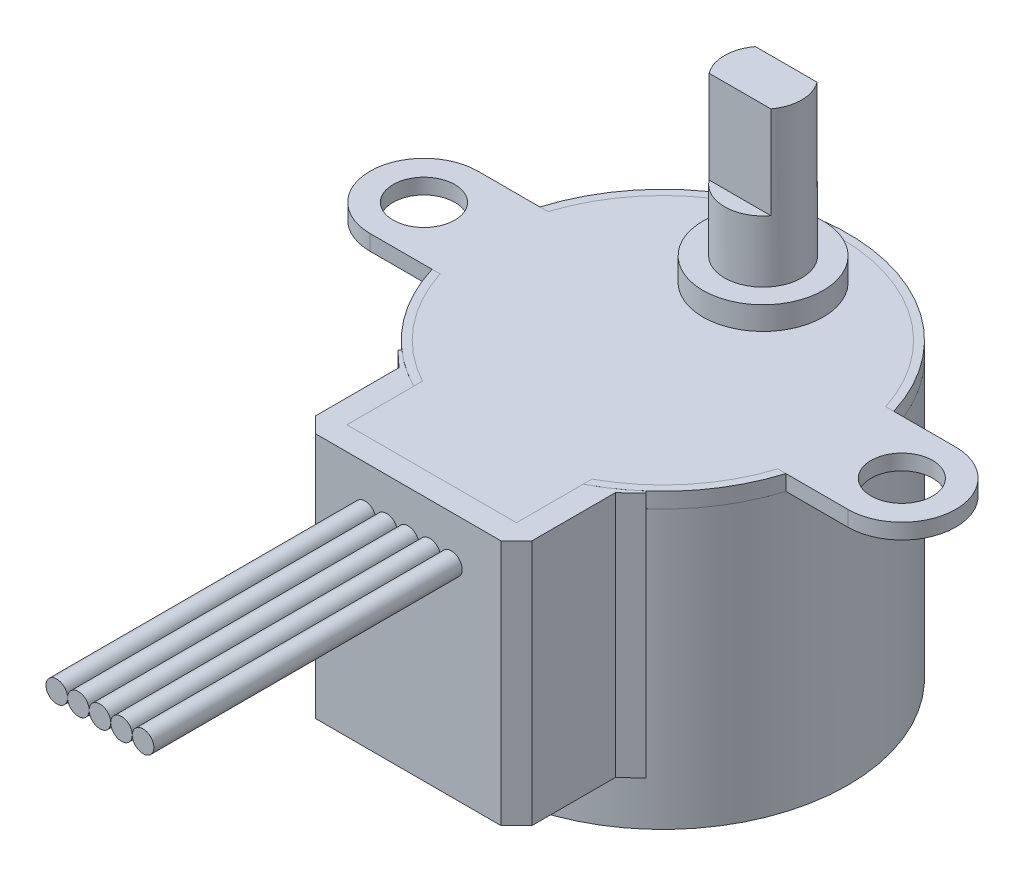
SolidWorks part; units mm, degrees
ref_plane "Front Plane" through (0, 0, 0) normal (0, 0, 1) x (1, 0, 0)
ref_plane "Top Plane" through (0, 0, 0) normal (0, 1, 0) x (1, 0, 0)
ref_plane "Right Plane" through (0, 0, 0) normal (1, 0, 0) x (0, 0, -1)
sketch "Sketch1" plane through (0, 0, 0) normal (0, 1, 0) x (1, 0, 0)
  circle A0 centre (0, 0) radius 12
  dimension "D1" = 24
extrude "Boss-Extrude1" add sketch "Sketch1" along normal blind 18
sketch "Sketch2" plane through (0, 18, 0) normal (0, 1, 0) x (1, 0, 0)
  line L0 (0, 16.9887) -> (0, 11.5) construction
  line L1 (10.9545, 3.5) -> (15.5, 3.5)
  line L2 (15.5, -3.5) -> (10.9545, -3.5)
  line L3 (-15.5, -3.5) -> (-10.9545, -3.5)
  line L4 (-10.9545, 3.5) -> (-15.5, 3.5)
  line L5 (-5.5, -10.0995) -> (-5.5, -15)
  line L6 (-5.5, -15) -> (5.5, -15)
  line L7 (5.5, -10.0995) -> (5.5, -15)
  line L8 (0, -11.5) -> (0, -20.5487) construction
  arc A0 (10.9545, 3.5) -> (-10.9545, 3.5) centre (0, 0) ccw
  circle A1 centre (15.5, 0) radius 2
  arc A2 (15.5, -3.5) -> (15.5, 3.5) centre (15.5, 0) ccw
  arc A3 (-15.5, -3.5) -> (-15.5, 3.5) centre (-15.5, 0) cw
  circle A4 centre (-15.5, 0) radius 2
  arc A5 (-10.9545, -3.5) -> (-5.5, -10.0995) centre (0, 0) ccw
  arc A6 (5.5, -10.0995) -> (10.9545, -3.5) centre (0, 0) ccw
  point P20 (0, -15)
  dimension "D1" = 23
  dimension "D3" = 4
  dimension "D2" = 15.5
  dimension "D4" = 3.5
  dimension "D5" = 7
  dimension "D6" = 15
  dimension "D7" = 5.5
extrude "Boss-Extrude2" add sketch "Sketch2" along normal blind 1 separate body
sketch "Sketch3" plane through (0, 18, 0) normal (0, 1, 0) x (1, 0, 0)
  line L0 (-11.4782, 3.5) -> (-10.9545, 3.5)
  line L3 (11.4782, -3.5) -> (10.9545, -3.5)
  line L5 (10.9545, 3.5) -> (11.4782, 3.5)
  line L6 (-10.9545, -3.5) -> (-11.4782, -3.5)
  line L7 (-5.5, -10.0995) -> (-5.5, -10.6654)
  line L8 (-5.5, -10.0995) -> (-5.5, -15) construction
  line L9 (5.5, -10.0995) -> (5.5, -10.6654)
  line L10 (5.5, -15) -> (5.5, -10.0995) construction
  arc A0 (-10.9545, -3.5) -> (-5.5, -10.0995) centre (0, 0) ccw
  circle A1 centre (0, 0) radius 12
  arc A2 (-11.4782, -3.5) -> (-5.5, -10.6654) centre (0, 0) ccw
  arc A3 (10.9545, 3.5) -> (-10.9545, 3.5) centre (0, 0) ccw
  arc A4 (11.4782, 3.5) -> (-11.4782, 3.5) centre (0, 0) ccw
  arc A5 (5.5, -10.0995) -> (10.9545, -3.5) centre (0, 0) ccw
  arc A6 (5.5, -10.6654) -> (11.4782, -3.5) centre (0, 0) ccw
  dimension "D1" = 0
extrude "Boss-Extrude3" add sketch "Sketch3" along normal blind 1 separate body
sketch "Sketch4" plane through (0, 19, 0) normal (0, 1, 0) x (1, 0, 0)
  line L0 (5.5, -15) -> (5.5, -10.0995) construction
  line L1 (-5.5, -15) -> (5.5, -15) construction
  line L2 (-5.5, -10.0995) -> (-5.5, -15) construction
  line L3 (5.5, -15) -> (5.5, -10.6654)
  line L4 (-5.5, -15) -> (5.5, -15)
  line L5 (-5.5, -10.6654) -> (-5.5, -15)
  line L6 (-7.02, -10.0995) -> (-7.02, -15.52)
  line L7 (-6.02, -16.52) -> (6.02, -16.52)
  line L8 (7.02, -15.52) -> (7.02, -10.0995)
  line L9 (-7.02, -10.0995) -> (-8.0447, -9.145)
  line L10 (-8.0447, -9.145) -> (-7.9259, -9.01)
  line L11 (0, 0) -> (0, -6.5603) construction
  line L12 (8.0447, -9.145) -> (7.9259, -9.01)
  line L13 (7.02, -10.0995) -> (8.0447, -9.145)
  line L14 (-5.5, -10.0995) -> (-5.5, -15) construction
  line L15 (5.5, -15) -> (5.5, -10.0995) construction
  line L16 (-7.02, -10.0995) -> (-7.02, -16.52) construction
  line L17 (-7.02, -16.52) -> (7.02, -16.52) construction
  line L18 (-7.02, -15.52) -> (-6.02, -16.52)
  line L19 (7.02, -16.52) -> (7.02, -10.0995) construction
  line L20 (6.02, -16.52) -> (7.02, -15.52)
  arc A0 (-7.9259, -9.01) -> (-5.5, -10.6654) centre (0, 0) ccw
  arc A1 (5.5, -10.6654) -> (7.9259, -9.01) centre (0, 0) ccw
  dimension "D1" = 1.52
extrude "Boss-Extrude4" add sketch "Sketch4" against normal blind 16 separate body
sketch "Sketch5" plane through (0, 3, 0) normal (0, -1, 0) x (1, 0, 0)
  line L12 (-5.5, 10.6654) -> (-5.5, 15)
  line L13 (-5.5, 15) -> (5.5, 15)
  line L14 (5.5, 15) -> (5.5, 10.6654)
  line L15 (7.9259, 9.01) -> (8.0447, 9.145)
  line L16 (8.0447, 9.145) -> (7.02, 10.0995)
  line L17 (7.02, 10.0995) -> (7.02, 15.52)
  line L18 (7.02, 15.52) -> (6.02, 16.52)
  line L19 (6.02, 16.52) -> (-6.02, 16.52)
  line L20 (-6.02, 16.52) -> (-7.02, 15.52)
  line L21 (-7.02, 15.52) -> (-7.02, 10.0995)
  line L22 (-7.02, 10.0995) -> (-8.0447, 9.145)
  line L23 (-8.0447, 9.145) -> (-7.9259, 9.01)
  line L27 (7.9259, 9.01) -> (8.0447, 9.145)
  line L28 (8.0447, 9.145) -> (7.02, 10.0995)
  line L29 (7.02, 10.0995) -> (7.02, 15.52)
  line L30 (7.02, 15.52) -> (6.02, 16.52)
  line L31 (6.02, 16.52) -> (-6.02, 16.52)
  line L32 (-6.02, 16.52) -> (-7.02, 15.52)
  line L33 (-7.02, 15.52) -> (-7.02, 10.0995)
  line L34 (-7.02, 10.0995) -> (-8.0447, 9.145)
  line L35 (-8.0447, 9.145) -> (-7.9259, 9.01)
  arc A0 (7.9259, 9.01) -> (-7.9259, 9.01) centre (0, 0) ccw
  arc A2 (-5.5, 10.6654) -> (-7.9259, 9.01) centre (0, 0) ccw
  arc A3 (7.9259, 9.01) -> (5.5, 10.6654) centre (0, 0) ccw
  arc A4 (-5.5, 10.6654) -> (-7.9259, 9.01) centre (0, 0) ccw
  arc A5 (7.9259, 9.01) -> (5.5, 10.6654) centre (0, 0) ccw
  arc M15 (-7.9259, 9.01) -> (-5.5, 10.6654) centre (0, 0) cw
  line M16 (-5.5, 10.6654) -> (-5.5, 15)
  line M17 (-5.5, 15) -> (5.5, 15)
  line M18 (5.5, 15) -> (5.5, 10.6654)
  arc M19 (5.5, 10.6654) -> (7.9259, 9.01) centre (0, 0) cw
  line M20 (7.9259, 9.01) -> (8.0447, 9.145)
  line M21 (8.0447, 9.145) -> (7.02, 10.0995)
  line M22 (7.02, 10.0995) -> (7.02, 15.52)
  line M23 (7.02, 15.52) -> (6.02, 16.52)
  line M24 (6.02, 16.52) -> (-6.02, 16.52)
  line M25 (-6.02, 16.52) -> (-7.02, 15.52)
  line M26 (-7.02, 15.52) -> (-7.02, 10.0995)
  line M27 (-7.02, 10.0995) -> (-8.0447, 9.145)
  line M28 (-8.0447, 9.145) -> (-7.9259, 9.01)
  dimension "D1" = 0
extrude "Boss-Extrude5" add sketch "Sketch5" against normal blind 1 contours A0 M18 M17 M16 | M28 M15 M16 M17 M18 M19 M20 M21 M22 M23 M24 M25 M26 M27
sketch "Sketch6" plane through (0, 19, 0) normal (0, 1, 0) x (1, 0, 0)
  circle A0 centre (0, 6.5) radius 3.9
  dimension "D2" = 7.8
  dimension "D1" = 6.5
extrude "Boss-Extrude6" add sketch "Sketch6" along normal blind 1.5 separate body
sketch "Sketch7" plane through (0, 20.5, 0) normal (0, 1, 0) x (1, 0, 0)
  circle A0 centre (0, 6.5) radius 2.5
  dimension "D1" = 5
extrude "Boss-Extrude7" add sketch "Sketch7" along normal blind 4 separate body
sketch "Sketch8" plane through (0, 24.5, 0) normal (0, 1, 0) x (1, 0, 0)
  line L0 (-2, 8) -> (2, 8)
  line L1 (-2, 5) -> (2, 5)
  arc A0 (2, 5) -> (2, 8) centre (0, 6.5) ccw
  circle A1 centre (0, 6.5) radius 2.5
  arc A2 (-2, 8) -> (-2, 5) centre (0, 6.5) ccw
  dimension "D2" = 1.5
  dimension "D3" = 1.5
  dimension "D1" = 0
extrude "Boss-Extrude8" add sketch "Sketch8" along normal blind 6
sketch "Sketch9" plane through (0, 0, 16.52) normal (0, 0, 1) x (1, 0, 0)
  line L0 (-6.02, 19) -> (6.02, 19) construction
  circle A0 centre (-2.8, 16.1282) radius 0.7
  point P12 (0, 19)
  dimension "D1" = 1.4
  dimension "D3" = 2.8
extrude "Boss-Extrude9" add sketch "Sketch9" along normal blind 20 separate body
pattern_linear "LPattern1" count 5 spacing 1.4 along (1, 0, 0) of bodies 112
